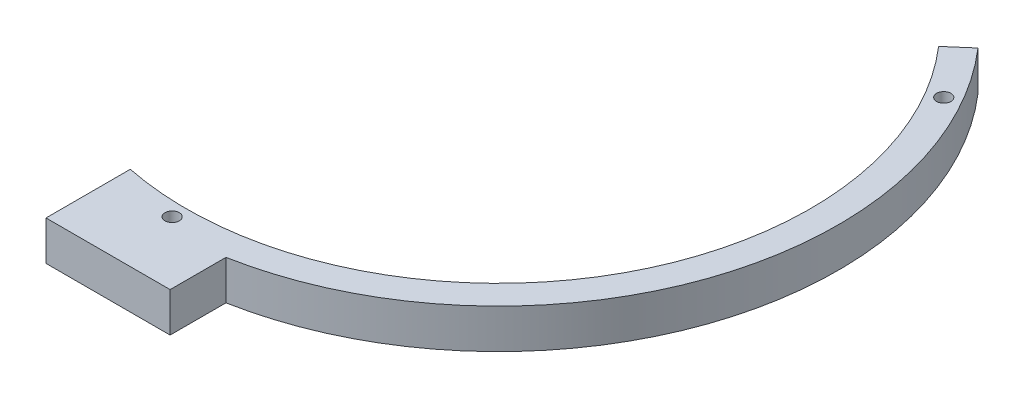
SolidWorks part; units mm, degrees
ref_plane "Front Plane" through (0, 0, 0) normal (0, 0, 1) x (1, 0, 0)
ref_plane "Top Plane" through (0, 0, 0) normal (0, 1, 0) x (1, 0, 0)
ref_plane "Right Plane" through (0, 0, 0) normal (1, 0, 0) x (0, 0, -1)
sketch "Sketch1" plane through (0, 0, 0) normal (0, 1, 0) x (1, 0, 0)
  line L0 (-10, -53.8799) -> (-10, -62.8799)
  line L1 (-10, -62.8799) -> (10, -62.8799)
  line L2 (10, -62.8799) -> (10, -53.8799)
  arc A0 (10, -53.8799) -> (-10, -53.8799) centre (0, 0) ccw
  circle A1 centre (0, 0) radius 50.3
  point P9 (0, -62.8799)
  dimension "D1" = 4.5
  dimension "D2" = 109.6
  dimension "D3" = 20
  dimension "D4" = 9
extrude "Boss-Extrude1" add sketch "Sketch1" along normal blind 6.35
sketch "Sketch2" plane through (0, 6.35, 0) normal (0, 1, 0) x (1, 0, 0)
  line L0 (0, -50.3) -> (0, -54.8) construction
  circle A0 centre (0, 0) radius 50.3 construction
  circle A1 centre (0, 0) radius 54.8 construction
  circle A2 centre (0, -52.55) radius 1.15
  dimension "D1" = 2.3
extrude "Cut-Extrude1" cut sketch "Sketch2" against normal up to next
pattern_circular "CirPattern1" count 3 over 360 about axis through (0, 0, 0) along (0, 1, 0) of "Cut-Extrude1"
sketch "Sketch3" plane through (0, 6.35, 0) normal (0, 1, 0) x (1, 0, 0)
  line L0 (-10, -53.8799) -> (-10, -49.2959)
  line L1 (41.3769, 35.9304) -> (37.9792, 32.9799)
  line L2 (0, 0) -> (41.3769, 35.9304) construction
  circle A0 centre (0, 0) radius 50.3 construction
  arc A1 (10, -53.8799) -> (-10, -53.8799) centre (0, 0) ccw construction
  circle A2 centre (0, 0) radius 54.8
  circle A3 centre (45.5096, 26.275) radius 1.15 construction
  circle A4 centre (0, 0) radius 50.3
  circle M5 centre (-45.5096, 26.275) radius 1.15
  arc M7 (10, -53.8799) -> (-10, -53.8799) centre (0, 0) ccw
  circle M11 centre (0, 0) radius 50.3
  dimension "D1" = 10
extrude "Cut-Extrude2" cut sketch "Sketch3" against normal up to next contours L1 L0 M7 M11 M5
